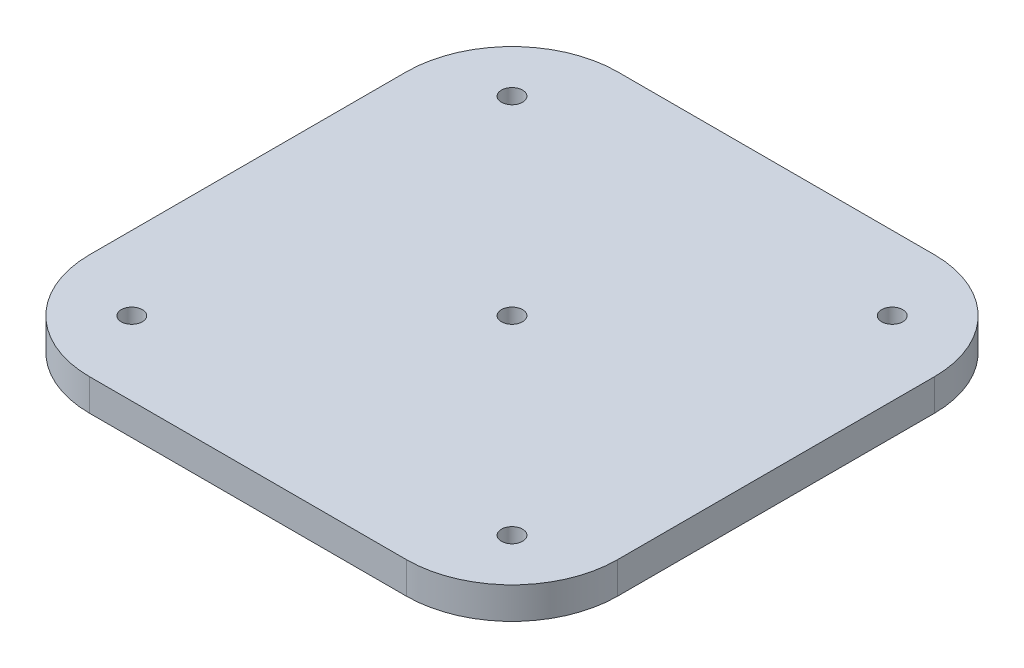
SolidWorks part; units mm, degrees
ref_plane "正面" through (0, 0, 0) normal (0, 0, 1) x (1, 0, 0)
ref_plane "平面" through (0, 0, 0) normal (0, 1, 0) x (1, 0, 0)
ref_plane "右側面" through (0, 0, 0) normal (1, 0, 0) x (0, 0, -1)
sketch "ｽｹｯﾁ4" plane through (0, 0, 0) normal (0, 1, 0) x (1, 0, 0)
  line L0 (13.643, 25.9499) -> (-16.357, 25.9499)
  line L1 (-26.357, 15.9499) -> (-26.357, -14.0501)
  line L2 (-16.357, -24.0501) -> (13.643, -24.0501)
  line L3 (23.643, -14.0501) -> (23.643, 15.9499)
  line L4 (-1.357, 25.9499) -> (-1.357, -24.0501) construction
  line L5 (-26.357, 0.9499) -> (23.643, 0.9499) construction
  arc A0 (-16.357, 25.9499) -> (-26.357, 15.9499) centre (-16.357, 15.9499) ccw
  arc A1 (-26.357, -14.0501) -> (-16.357, -24.0501) centre (-16.357, -14.0501) ccw
  arc A2 (13.643, -24.0501) -> (23.643, -14.0501) centre (13.643, -14.0501) ccw
  arc A3 (23.643, 15.9499) -> (13.643, 25.9499) centre (13.643, 15.9499) ccw
  circle A4 centre (16.643, -17.0501) radius 1
  circle A5 centre (16.643, 18.9499) radius 1
  circle A6 centre (-19.357, 18.9499) radius 1
  circle A7 centre (-19.357, -17.0501) radius 1
  circle A8 centre (-1.357, 0.9499) radius 1
  dimension "D1" = 2
  dimension "D3" = 36
  dimension "D5" = 36
  dimension "D7" = 7
  dimension "D8" = 2
  dimension "D9" = 2
  dimension "D10" = 2
  dimension "D11" = 2
  dimension "D2" = 50
  dimension "D4" = 7
  dimension "D6" = 50
extrude "ﾎﾞｽ - 押し出し1" add sketch "ｽｹｯﾁ4" along normal blind 3
